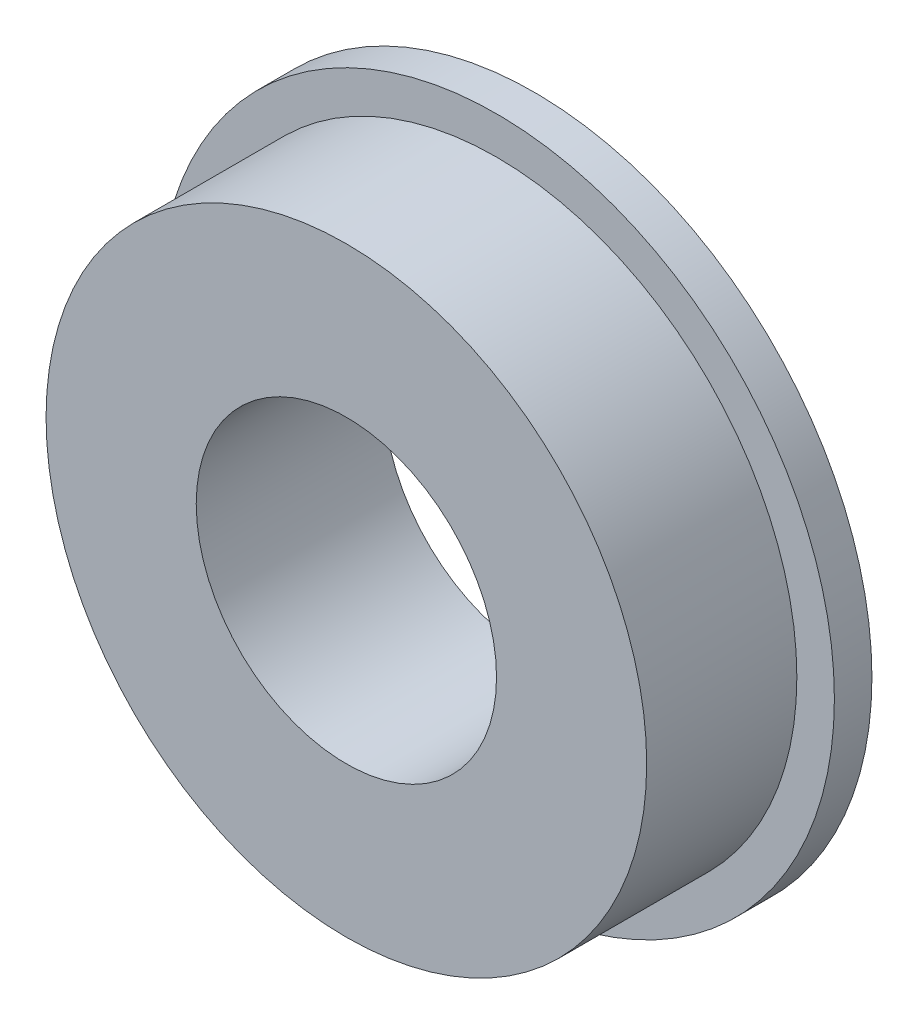
SolidWorks part; units mm, degrees
ref_plane "Спереди" through (0, 0, 0) normal (0, 0, 1) x (1, 0, 0)
ref_plane "Сверху" through (0, 0, 0) normal (0, 1, 0) x (1, 0, 0)
ref_plane "Справа" through (0, 0, 0) normal (1, 0, 0) x (0, 0, -1)
sketch "Эскиз1" plane through (0, 0, 0) normal (0, 0, 1) x (1, 0, 0)
  circle A0 centre (0, 0) radius 9
  circle A1 centre (0, 0) radius 4
  dimension "D1" = 18
  dimension "D2" = 8
extrude "Бобышка-Вытянуть1" add sketch "Эскиз1" along normal blind 5
sketch "Эскиз2" plane through (0, 0, 5) normal (0, 0, 1) x (1, 0, 0)
  circle A0 centre (0, 0) radius 8
  circle A1 centre (0, 0) radius 9
  circle A4 centre (0, 0) radius 9 construction
  dimension "D1" = 16
extrude "Вырез-Вытянуть1" cut sketch "Эскиз2" against normal offset from surface (4 mm away) 1 up to face at (9, 0, 0)
